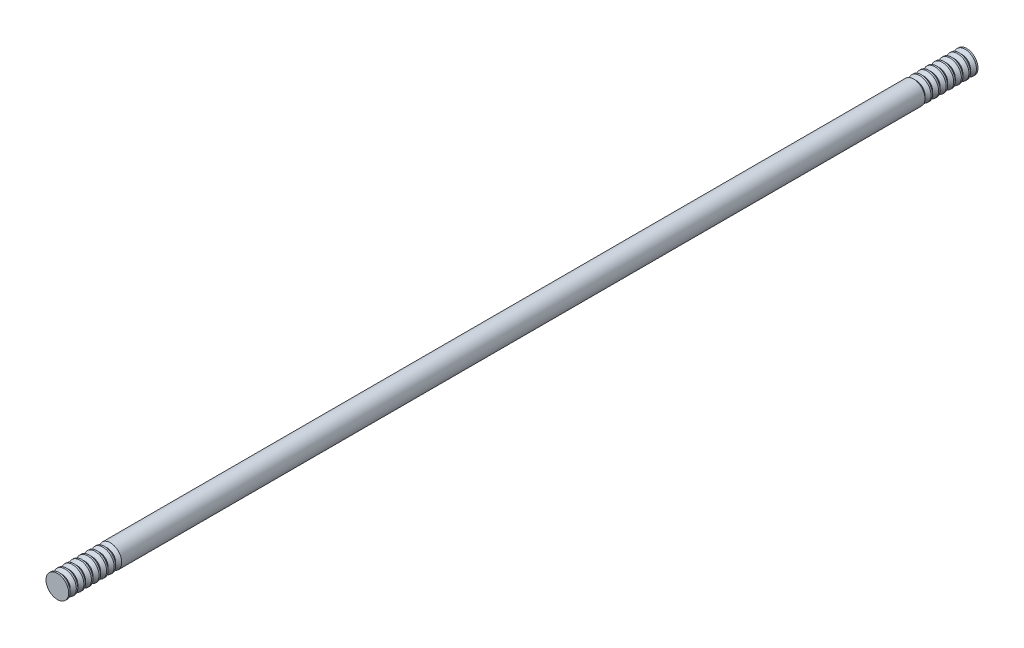
SolidWorks part; units mm, degrees
ref_plane "Front Plane" through (0, 0, 0) normal (0, 0, 1) x (1, 0, 0)
ref_plane "Top Plane" through (0, 0, 0) normal (0, 1, 0) x (1, 0, 0)
ref_plane "Right Plane" through (0, 0, 0) normal (1, 0, 0) x (0, 0, -1)
sketch "Sketch1" plane through (0, 0, 0) normal (0, 0, 1) x (1, 0, 0)
  circle A0 centre (0, 0) radius 1.5
  dimension "D1" = 3
extrude "Boss-Extrude1" add sketch "Sketch1" along normal mid plane 120
sketch "Sketch2" plane through (0, 0, 0) normal (1, 0, 0) x (0, 0, -1)
  line L0 (59.8, -1.5) -> (59.4, -1.1)
  line L1 (-60, -1.5) -> (60, -1.5) construction
  line L2 (59.4, -1.1) -> (59, -1.5)
  line L3 (59, -1.5) -> (59, -1.8983)
  line L4 (59, -1.8983) -> (59.8, -1.8983)
  line L5 (59.8, -1.8983) -> (59.8, -1.5)
  line L6 (60, -1.5) -> (60, 1.5) construction
  dimension "D1" = 0.8
  dimension "D2" = 0.4
  dimension "D3" = 0.4
  dimension "D4" = 0.3983
  dimension "D5" = 0.2
revolve "Cut-Revolve1" cut sketch "Sketch2" angle 360 about axis through (0, 0, 60) along (0, 0, -1)
pattern_linear "LPattern1" count 7 spacing 1 along (0, 0, 1) of "Cut-Revolve1"
mirror "Mirror1" about plane through (0, 0, 0) normal (0, 0, 1) of "Cut-Revolve1", "LPattern1"
